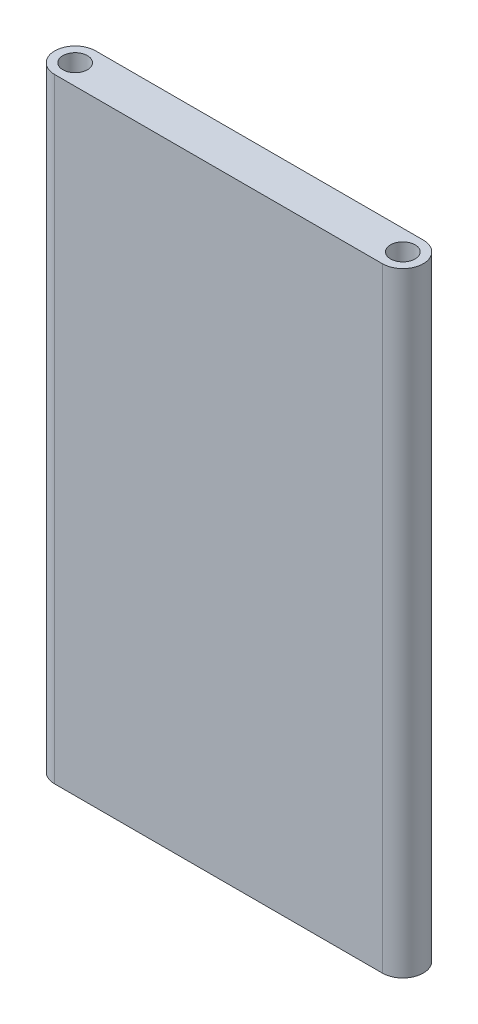
SolidWorks part; units mm, degrees
ref_plane "Front Plane" through (0, 0, 0) normal (0, 0, 1) x (1, 0, 0)
ref_plane "Top Plane" through (0, 0, 0) normal (0, 1, 0) x (1, 0, 0)
ref_plane "Right Plane" through (0, 0, 0) normal (1, 0, 0) x (0, 0, -1)
sketch "Sketch1" plane through (0, 0, 0) normal (0, 1, 0) x (1, 0, 0)
  line L0 (0, 0) -> (0, 6.35) construction
  line L1 (0, 6.35) -> (50.8, 6.35)
  line L4 (50.8, -6.35) -> (-50.8, -6.35)
  line L5 (0, 6.35) -> (-50.8, 6.35)
  circle A2 centre (-50.8, 0) radius 3.81
  arc A3 (-50.8, -6.35) -> (-50.8, 6.35) centre (-50.8, 0) cw
  arc A4 (50.8, -6.35) -> (50.8, 6.35) centre (50.8, 0) ccw
  circle A5 centre (50.8, 0) radius 3.81
  point P4 (0, 0)
  point P5 (0, 6.35)
  dimension "D6" = 50.8
  dimension "D7" = 6.35
  dimension "D10" = 7.62
  dimension "D1" = 6.35
  dimension "D5" = 101.6
  dimension "D8" = 6.35
extrude "Boss-Extrude1" add sketch "Sketch1" along normal mid plane 190.5
